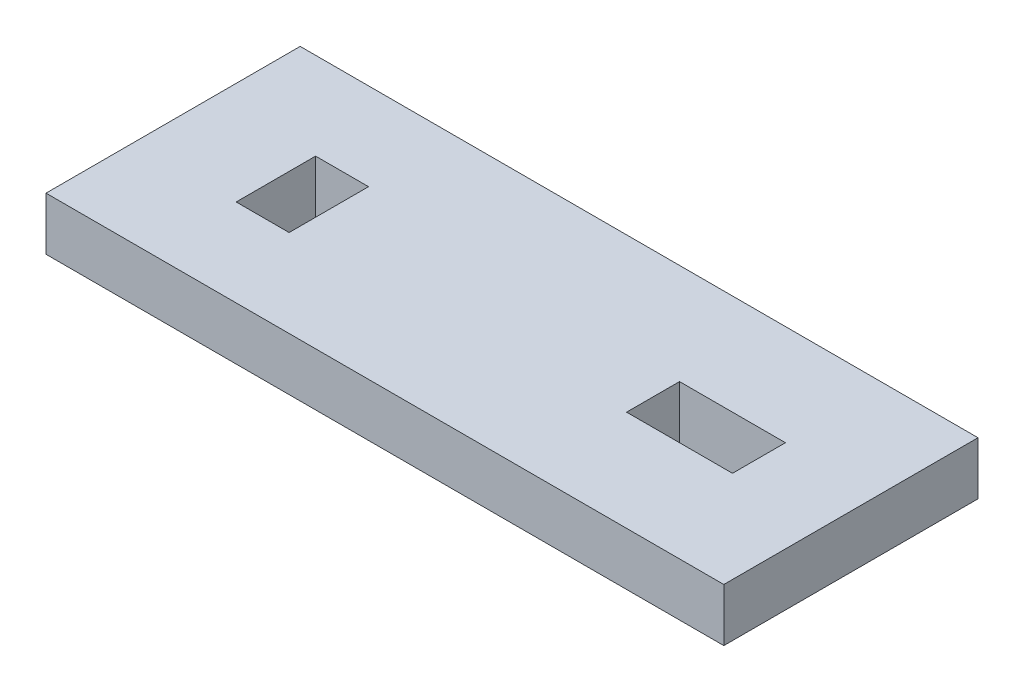
SolidWorks part; units mm, degrees
material "Balsa"
ref_plane "Front Plane" through (0, 0, 0) normal (0, 0, 1) x (1, 0, 0)
ref_plane "Top Plane" through (0, 0, 0) normal (0, 1, 0) x (1, 0, 0)
ref_plane "Right Plane" through (0, 0, 0) normal (1, 0, 0) x (0, 0, -1)
sketch "Sketch1" plane through (0, 0, 0) normal (0, 1, 0) x (1, 0, 0)
  line L1 (0, 0) -> (40.64, 0)
  line L2 (0, 0) -> (0, 15.24)
  line L3 (0, 15.24) -> (40.64, 15.24)
  line L4 (40.64, 0) -> (40.64, 15.24)
  dimension "0.6" = 15.24
  dimension "D2" = 40.64
extrude "Boss-Extrude1" add sketch "Sketch1" along normal blind 3.175
sketch "Sketch2" plane through (0, 3.175, 0) normal (0, 1, 0) x (1, 0, 0)
  line L0 (28.777, 6.0325) -> (35.127, 6.0325) construction
  line L1 (35.127, 6.0325) -> (35.127, 9.2075) construction
  line L2 (28.777, 9.2075) -> (28.777, 6.0325) construction
  line L3 (35.127, 9.2075) -> (28.777, 9.2075) construction
  line L4 (6.1595, 10.0047) -> (6.1595, 5.2422) construction
  line L5 (9.3345, 10.0047) -> (6.1595, 10.0047) construction
  line L6 (6.1595, 5.2422) -> (9.3345, 5.2422) construction
  line L7 (9.3345, 5.2422) -> (9.3345, 10.0047) construction
  line L8 (28.777, 6.0325) -> (35.127, 6.0325)
  line L9 (35.127, 6.0325) -> (35.127, 9.2075)
  line L10 (28.777, 9.2075) -> (28.777, 6.0325)
  line L11 (35.127, 9.2075) -> (28.777, 9.2075)
  line L12 (6.1595, 10.0047) -> (6.1595, 5.2422)
  line L13 (9.3345, 10.0047) -> (6.1595, 10.0047)
  line L14 (6.1595, 5.2422) -> (9.3345, 5.2422)
  line L15 (9.3345, 5.2422) -> (9.3345, 10.0047)
extrude "Cut-Extrude1" cut sketch "Sketch2" against normal through all
